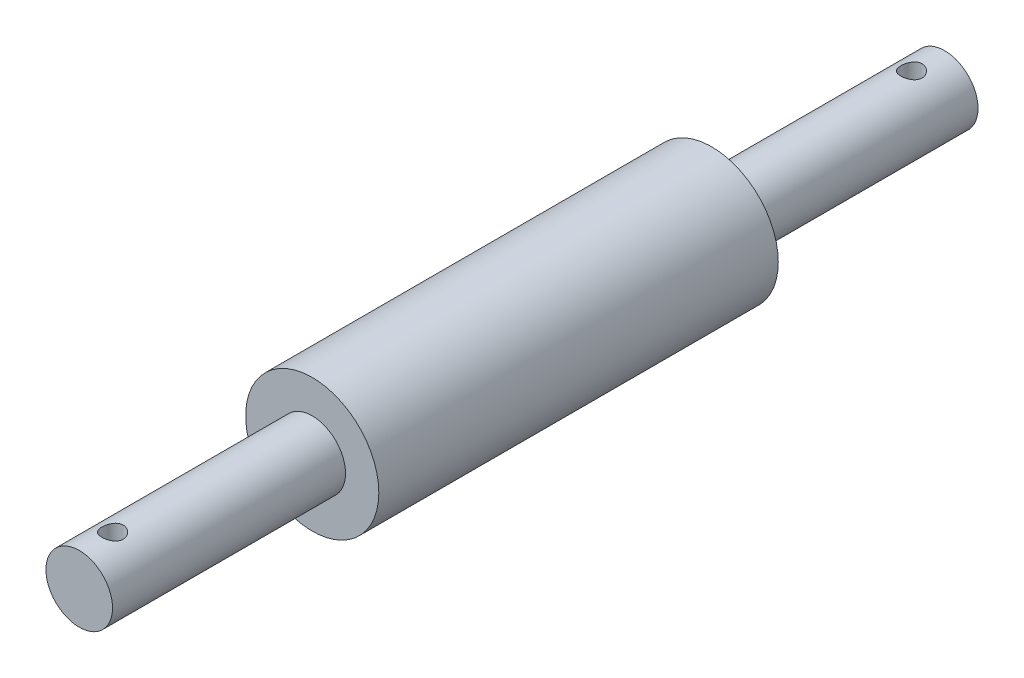
SolidWorks part; units mm, degrees
ref_plane "前视基准面" through (0, 0, 0) normal (0, 0, 1) x (1, 0, 0)
ref_plane "上视基准面" through (0, 0, 0) normal (0, 1, 0) x (1, 0, 0)
ref_plane "右视基准面" through (0, 0, 0) normal (1, 0, 0) x (0, 0, -1)
other "Configuration Table"
sketch "草图1" plane through (0, 0, 0) normal (0, 0, 1) x (1, 0, 0)
  circle A0 centre (0, 0) radius 5
  dimension "D1" = 10
extrude "凸台-拉伸1" add sketch "草图1" along normal blind 130
sketch "草图2" plane through (0, 0, 130) normal (0, 0, 1) x (1, 0, 0)
  circle A0 centre (0, 0) radius 10
  dimension "D1" = 20
extrude "凸台-拉伸2" add sketch "草图2" against normal offset from surface (60 mm away) 35 from offset 35 up to face at (5, 0, 0) offset against normal yes
sketch "草图3" plane through (0, 0, 0) normal (0, 1, 0) x (1, 0, 0)
  line L0 (5, 0) -> (-5, 0) construction
  line L1 (-5, -130) -> (5, -130) construction
  circle A0 centre (0, -5) radius 1.6
  circle A1 centre (0, -125) radius 1.6
  dimension "D2" = 3.2
  dimension "D3" = 3.2
  dimension "D1" = 5
  dimension "D4" = 5
extrude "切除-拉伸1" cut sketch "草图3" against normal through all both and the other way through all contours A1 | A0
